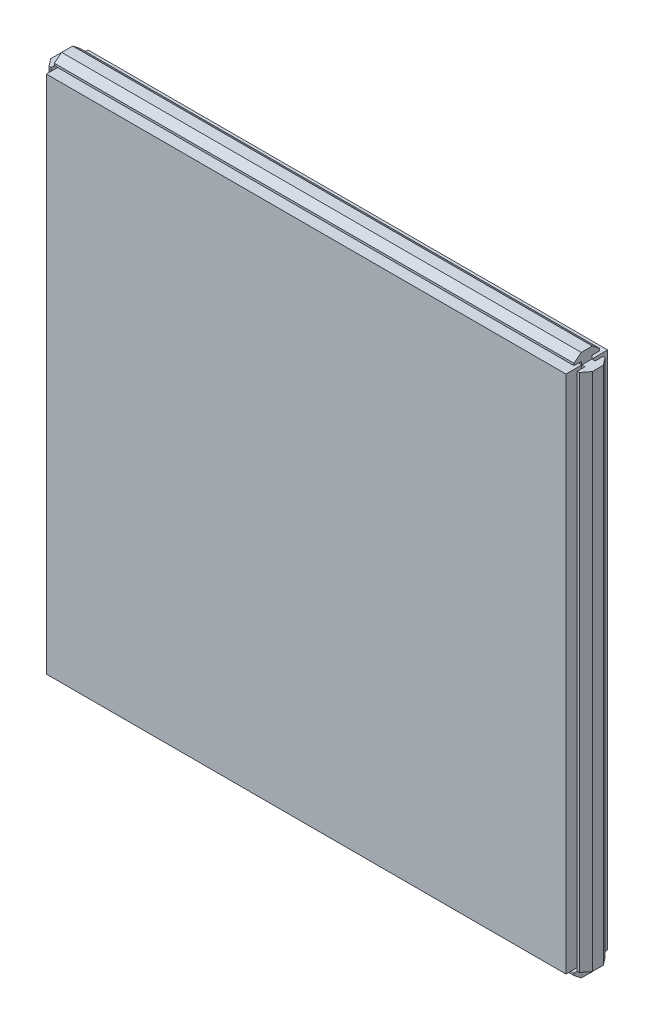
SolidWorks part; units mm, degrees
ref_plane "Plan de face" through (0, 0, 0) normal (0, 0, 1) x (1, 0, 0)
ref_plane "Plan de dessus" through (0, 0, 0) normal (0, 1, 0) x (1, 0, 0)
ref_plane "Plan de droite" through (0, 0, 0) normal (1, 0, 0) x (0, 0, -1)
sketch "Esquisse1" plane through (0, 0, 0) normal (0, 0, 1) x (1, 0, 0)
  line L0 (-179.1432, 44.1646) -> (69.8568, 44.1646)
  line L1 (69.8568, 44.1646) -> (69.8568, 38.8646)
  line L2 (69.8568, 38.8646) -> (75.1568, 38.8646)
  line L3 (75.1568, 38.8646) -> (75.1568, -210.1354)
  line L4 (75.1568, -210.1354) -> (69.8568, -210.1354)
  line L5 (69.8568, -210.1354) -> (69.8568, -215.4354)
  line L6 (69.8568, -215.4354) -> (-179.1432, -215.4354)
  line L7 (-179.1432, -215.4354) -> (-179.1432, -210.1354)
  line L8 (-179.1432, -210.1354) -> (-184.4432, -210.1354)
  line L9 (-184.4432, -210.1354) -> (-184.4432, 38.8646)
  line L10 (-184.4432, 38.8646) -> (-179.1432, 38.8646)
  line L11 (-179.1432, 38.8646) -> (-179.1432, 44.1646)
  point P14 (-243.6721, 57.8626)
  dimension "D1" = 249
  dimension "D2" = 5.3
  dimension "D3" = 5.3
  dimension "D4" = 249
  dimension "D5" = 5.3
  dimension "D6" = 5.3
  dimension "D7" = 249
  dimension "D8" = 5.3
  dimension "D9" = 5.3
  dimension "D10" = 249
  dimension "D11" = 5.3
  dimension "D12" = 5.3
extrude "Boss.-Extru.1" add sketch "Esquisse1" along normal blind 20
sketch "Esquisse2" plane through (-179.1432, 0, 0) normal (-1, 0, 0) x (0, 0, 1)
  line L0 (0, 38.8646) -> (7.55, 38.8646)
  line L1 (20, 38.8646) -> (0, 38.8646) construction
  line L2 (7.55, 38.8646) -> (7.55, 40.4146)
  line L3 (7.55, 40.4146) -> (3.85, 40.4146)
  line L4 (3.85, 40.4146) -> (3.85, 41.4146)
  line L5 (3.85, 41.4146) -> (7.35, 44.1646)
  line L6 (20, 44.1646) -> (0, 44.1646) construction
  dimension "D1" = 7.55
  dimension "D2" = 1.55
  dimension "D3" = 3.7
  dimension "D4" = 1
  dimension "D5" = 7.35
extrude "Enlèv. mat.-Extru.1" cut sketch "Esquisse2" against normal blind 249 and the other way through all
sketch "Esquisse3" plane through (-179.1432, 0, 0) normal (-1, 0, 0) x (0, 0, 1)
  line L0 (20, 38.8646) -> (12.45, 38.8646)
  line L1 (20, 38.8646) -> (7.55, 38.8646) construction
  line L2 (12.45, 38.8646) -> (12.45, 40.4146)
  line L3 (12.45, 40.4146) -> (16.15, 40.4146)
  line L4 (16.15, 40.4146) -> (16.15, 41.4146)
  line L5 (16.15, 41.4146) -> (12.65, 44.1646)
  line L6 (20, 44.1646) -> (7.35, 44.1646) construction
  dimension "D1" = 7.55
  dimension "D2" = 1.55
  dimension "D3" = 3.7
  dimension "D4" = 1
  dimension "D5" = 7.35
extrude "Enlèv. mat.-Extru.2" cut sketch "Esquisse3" against normal blind 249 and the other way through all flip side to cut
sketch "Esquisse5" plane through (0, -210.1354, 0) normal (0, -1, 0) x (-1, 0, 0)
  line L0 (179.1432, -20) -> (179.1432, 0) construction
  line L1 (179.1432, 0) -> (179.1432, -7.55)
  line L2 (179.1432, -7.55) -> (180.6932, -7.55)
  line L3 (180.6932, -7.55) -> (180.6932, -3.85)
  line L4 (180.6932, -3.85) -> (181.6932, -3.85)
  line L5 (181.6932, -3.85) -> (184.4432, -7.35)
  line L6 (184.4432, -20) -> (184.4432, 0) construction
  dimension "D1" = 7.55
  dimension "D2" = 1.55
  dimension "D3" = 3.7
  dimension "D4" = 1
  dimension "D5" = 7.35
extrude "Enlèv. mat.-Extru.3" cut sketch "Esquisse5" against normal blind 249 and the other way through all
sketch "Esquisse6" plane through (0, -210.1354, 0) normal (0, -1, 0) x (-1, 0, 0)
  line L0 (179.1432, -12.45) -> (179.1432, -20)
  line L1 (179.1432, -20) -> (179.1432, -7.55) construction
  line L2 (179.1432, -12.45) -> (180.6932, -12.45)
  line L3 (180.6932, -12.45) -> (180.6932, -16.15)
  line L4 (180.6932, -16.15) -> (181.6932, -16.15)
  line L5 (181.6932, -16.15) -> (184.4432, -12.65)
  line L6 (184.4432, -20) -> (184.4432, -7.35) construction
  dimension "D1" = 7.55
  dimension "D2" = 1.55
  dimension "D3" = 3.7
  dimension "D4" = 1
  dimension "D5" = 7.35
extrude "Enlèv. mat.-Extru.4" cut sketch "Esquisse6" against normal blind 249 and the other way through all flip side to cut
sketch "Esquisse8" plane through (-179.1432, 0, 0) normal (-1, 0, 0) x (0, 0, 1)
  line L0 (12.45, -210.1354) -> (20, -210.1354)
  line L1 (20, 38.8646) -> (20, -215.4354) construction
  line L2 (12.45, -210.1354) -> (12.45, -211.6854)
  line L3 (12.45, -211.6854) -> (16.15, -211.6854)
  line L4 (16.15, -211.6854) -> (16.15, -212.6854)
  line L5 (16.15, -212.6854) -> (12.65, -215.4354)
  line L6 (20, -215.4354) -> (0, -215.4354) construction
  dimension "D1" = 7.55
  dimension "D2" = 1.55
  dimension "D3" = 3.7
  dimension "D4" = 1
  dimension "D5" = 7.35
extrude "Enlèv. mat.-Extru.5" cut sketch "Esquisse8" against normal blind 249 and the other way through all
sketch "Esquisse9" plane through (-179.1432, 0, 0) normal (-1, 0, 0) x (0, 0, 1)
  line L0 (7.55, -210.1354) -> (0, -210.1354)
  line L1 (0, 38.8646) -> (0, -215.4354) construction
  line L2 (7.55, -210.1354) -> (7.55, -211.6854)
  line L3 (7.55, -211.6854) -> (3.85, -211.6854)
  line L4 (3.85, -211.6854) -> (3.85, -212.6854)
  line L5 (3.85, -212.6854) -> (7.35, -215.4354)
  line L6 (12.65, -215.4354) -> (0, -215.4354) construction
  dimension "D1" = 7.55
  dimension "D2" = 1.55
  dimension "D3" = 3.7
  dimension "D4" = 1
  dimension "D5" = 7.35
extrude "Enlèv. mat.-Extru.6" cut sketch "Esquisse9" against normal blind 249 and the other way through all flip side to cut
sketch "Esquisse11" plane through (0, 38.8646, 0) normal (0, 1, 0) x (1, 0, 0)
  line L0 (69.8568, -7.55) -> (69.8568, 0)
  line L1 (75.1568, 0) -> (-179.1432, 0) construction
  line L2 (69.8568, -7.55) -> (71.4068, -7.55)
  line L3 (71.4068, -7.55) -> (71.4068, -3.85)
  line L4 (71.4068, -3.85) -> (72.4068, -3.85)
  line L5 (72.4068, -3.85) -> (75.1568, -7.35)
  line L6 (75.1568, -20) -> (75.1568, 0) construction
  dimension "D1" = 7.55
  dimension "D2" = 1.55
  dimension "D3" = 3.7
  dimension "D4" = 1
  dimension "D5" = 7.35
extrude "Enlèv. mat.-Extru.7" cut sketch "Esquisse11" against normal blind 249 and the other way through all
sketch "Esquisse12" plane through (0, 38.8646, 0) normal (0, 1, 0) x (1, 0, 0)
  line L0 (69.8568, -12.45) -> (69.8568, -20)
  line L1 (75.1568, -20) -> (-179.1432, -20) construction
  line L2 (69.8568, -12.45) -> (71.4068, -12.45)
  line L3 (71.4068, -12.45) -> (71.4068, -16.15)
  line L4 (71.4068, -16.15) -> (72.4068, -16.15)
  line L5 (72.4068, -16.15) -> (75.1568, -12.65)
  line L6 (75.1568, -20) -> (75.1568, -7.35) construction
  dimension "D1" = 7.55
  dimension "D2" = 1.55
  dimension "D3" = 3.7
  dimension "D4" = 1
  dimension "D5" = 7.35
extrude "Enlèv. mat.-Extru.8" cut sketch "Esquisse12" against normal blind 249 and the other way through all flip side to cut
